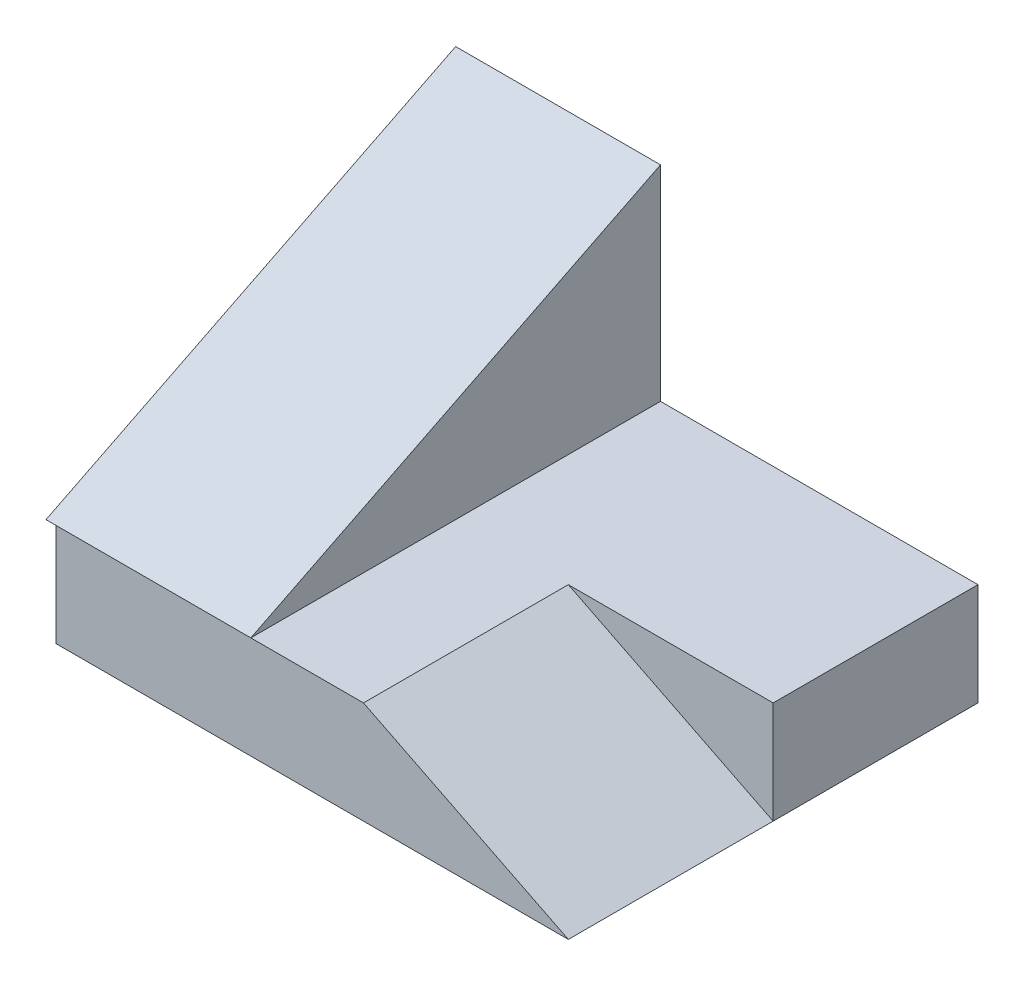
SolidWorks part; units mm, degrees
ref_plane "Front Plane" through (0, 0, 0) normal (0, 0, 1) x (1, 0, 0)
ref_plane "Top Plane" through (0, 0, 0) normal (0, 1, 0) x (1, 0, 0)
ref_plane "Right Plane" through (0, 0, 0) normal (1, 0, 0) x (0, 0, -1)
sketch "Sketch2" plane through (0, 0, 0) normal (0, 1, 0) x (1, 0, 0)
  line L1 (0, 0) -> (127, 0)
  line L2 (0, 0) -> (0, 101.6)
  line L3 (0, 101.6) -> (127, 101.6)
  line L4 (127, 0) -> (127, 101.6)
  dimension "D1" = 101.6
  dimension "D2" = 127
extrude "Boss-Extrude1" add sketch "Sketch2" along normal blind 25.4
sketch "Sketch4" plane through (0, 0, 0) normal (0, 0, 1) x (1, 0, 0)
  line L0 (0, 25.4) -> (127, 25.4) construction
  line L1 (127, 25.4) -> (127, 0) construction
  line L2 (76.2, 25.4) -> (127, 25.4)
  line L3 (127, 25.4) -> (127, 0)
  line L4 (76.2, 25.4) -> (127, 0)
  dimension "D1" = 50.8
extrude "Cut-Extrude2" cut sketch "Sketch4" against normal blind 50.8
ref_plane "Plane1" through (-2.54, 0, 0) normal (-1, 0, 0) x (0, 0, 1)
sketch "Sketch5" plane through (-2.54, 0, 0) normal (-1, 0, 0) x (0, 0, 1)
  line L0 (-101.6, 25.4) -> (0, 25.4) construction
  line L1 (-101.6, 25.4) -> (0, 25.4)
  line L2 (-101.6, 25.4) -> (-101.6, 76.2)
  line L3 (-101.6, 76.2) -> (0, 25.4)
  dimension "D1" = 50.8
extrude "Boss-Extrude2" add sketch "Sketch5" against normal blind 50.8
